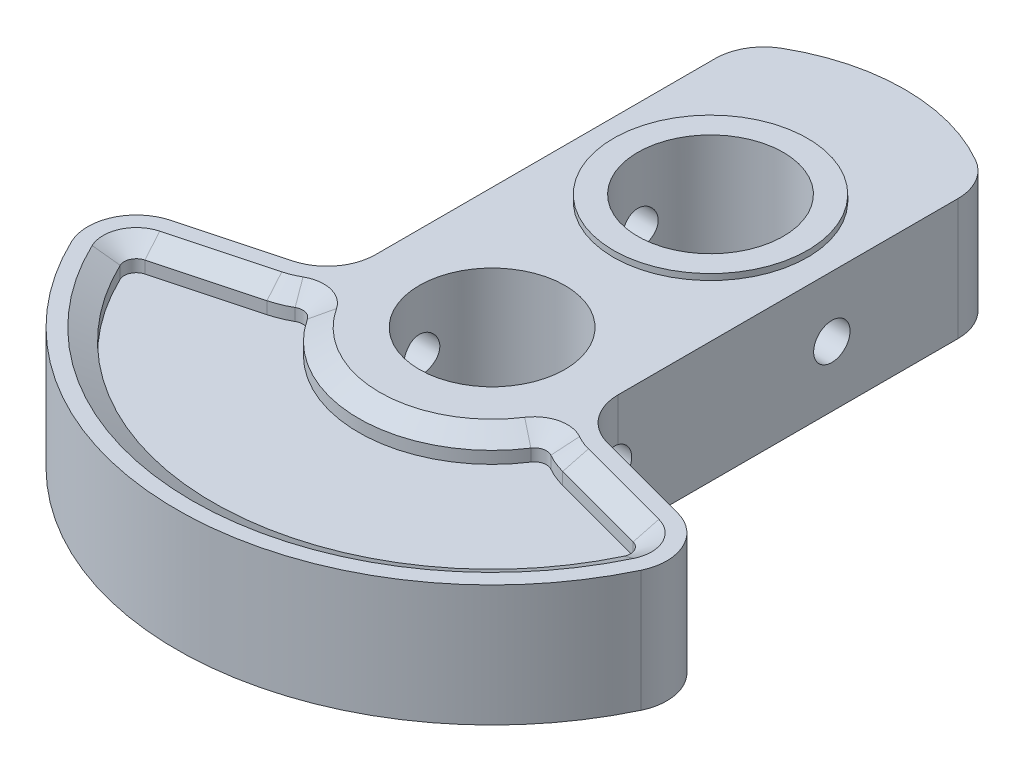
SolidWorks part; units mm, degrees
ref_plane "Front Plane" through (0, 0, 0) normal (0, 0, 1) x (1, 0, 0)
ref_plane "Top Plane" through (0, 0, 0) normal (0, 1, 0) x (1, 0, 0)
ref_plane "Right Plane" through (0, 0, 0) normal (1, 0, 0) x (0, 0, -1)
sketch "Sketch1" plane through (0, 0, 0) normal (0, 1, 0) x (1, 0, 0)
  line L0 (0, 41.1186) -> (0, -12.5062) construction
  line L1 (-10, 30.49) -> (-10, -2.6795)
  line L2 (10, 30.49) -> (10, -2.6795)
  line L3 (0, 0) -> (-25.1141, -6.7293) construction
  line L4 (-10, 41.1186) -> (-10, -12.5062) construction
  line L5 (10, 41.1186) -> (10, -12.5062) construction
  line L6 (0, 0) -> (25.1141, -6.7293) construction
  line L7 (-25.1141, -6.7293) -> (-10, -2.6795)
  line L8 (25.1141, -6.7293) -> (10, -2.6795)
  arc A0 (10, 30.49) -> (-10, 30.49) centre (0, 18) ccw
  arc A2 (-25.1141, -6.7293) -> (25.1141, -6.7293) centre (0, 0) ccw
  dimension "D1" = 18
  dimension "D2" = 10
  dimension "D4" = 26
  dimension "D5" = 75
  dimension "D6" = 75
  dimension "D3" = 10
extrude "Boss-Extrude1" add sketch "Sketch1" along normal mid plane 10
fillet "Fillet1" radius 4 6 edges at (-25.1141, 0, 6.7293) (-10, 0, 2.6795) (-10, 0, -30.49) (25.1141, 0, 6.7293) (10, 0, 2.6795) (10, 0, -30.49)
sketch "Sketch2" plane through (0, 0, 0) normal (0, 1, 0) x (1, 0, 0)
  circle A1 centre (0, 18) radius 8
  dimension "D1" = 18
extrude "Boss-Extrude2" add sketch "Sketch2" along normal mid plane 1
sketch "Sketch3" plane through (0, 5, 0) normal (0, 1, 0) x (1, 0, 0)
  circle A0 centre (0, 18) radius 8
  dimension "D1" = 18
extrude "Boss-Extrude3" add sketch "Sketch3" along normal mid plane 1
sketch "Sketch4" plane through (0, -5, 0) normal (0, -1, 0) x (1, 0, 0)
  circle A0 centre (0, 0) radius 8
extrude "Boss-Extrude4" add sketch "Sketch4" along normal mid plane 1
sketch "Sketch5" plane through (0, -5.5, 0) normal (0, -1, 0) x (-1, 0, 0)
  circle A0 centre (0, 0) radius 6
  circle A2 centre (0, 18) radius 6
extrude "Cut-Extrude1" cut sketch "Sketch5" against normal through all both
sketch "Sketch6" plane through (0, 5, 0) normal (0, 1, 0) x (1, 0, 0)
  line L0 (-12.9647, -3.4739) -> (-20.8962, -5.5991) construction
  line L6 (12.1883, -6.3717) -> (20.1197, -8.4969)
  line L7 (-20.1197, -8.4969) -> (-12.1883, -6.3717)
  line L8 (12.1883, -6.3717) -> (20.1197, -8.4969)
  line L9 (-20.1197, -8.4969) -> (-12.1883, -6.3717)
  arc A10 (-9.2082, -6.0173) -> (9.2082, -6.0173) centre (0, 0) ccw
  arc A11 (9.2082, -6.0173) -> (10.5397, -5.6951) centre (10.0453, -6.5644) cw
  arc A12 (-9.2082, -6.0173) -> (-10.5397, -5.6951) centre (-10.0453, -6.5644) ccw
  arc A15 (20.7637, -9.8929) -> (20.1197, -8.4969) centre (19.8609, -9.4628) ccw
  arc A16 (7, 0.3898) -> (12.1883, -6.3717) centre (14, 0.3898) ccw
  arc A17 (-12.1883, -6.3717) -> (-7, 0.3898) centre (-14, 0.3898) ccw
  arc A18 (-20.1197, -8.4969) -> (-20.7637, -9.8929) centre (-19.8609, -9.4628) ccw
  arc A19 (-20.7637, -9.8929) -> (20.7637, -9.8929) centre (0, 0) ccw
  arc A20 (20.7637, -9.8929) -> (20.1197, -8.4969) centre (19.8609, -9.4628) ccw
  arc A21 (10.5397, -5.6951) -> (12.1883, -6.3717) centre (14, 0.3898) ccw
  arc A22 (-12.1883, -6.3717) -> (-10.5397, -5.6951) centre (-14, 0.3898) ccw
  arc A23 (-20.1197, -8.4969) -> (-20.7637, -9.8929) centre (-19.8609, -9.4628) ccw
  arc A24 (-20.7637, -9.8929) -> (20.7637, -9.8929) centre (0, 0) ccw
  dimension "D2" = 1
  dimension "D1" = 3
extrude "Cut-Extrude2" cut sketch "Sketch6" against normal blind 2
mirror "Mirror7" about plane through (0, 0, 0) normal (0, 1, 0) of "Cut-Extrude2"
chamfer "Chamfer2" distance 1 angle 60 20 edges at (11.3424, 5, 6.0861) (9.8101, 5, 5.5924) (16.154, 5, 7.4343) (0, 5, 11) (20.7689, 5, 9.044) (-9.8101, 5, 5.5924) (0, 5, 23) (-11.3424, 5, 6.0861) (-20.7689, 5, 9.044) (-16.154, 5, 7.4343) (11.3424, -5, 6.0861) (9.8101, -5, 5.5924) (16.154, -5, 7.4343) (0, -5, 11) (20.7689, -5, 9.044) (-9.8101, -5, 5.5924) (0, -5, 23) (-11.3424, -5, 6.0861) (-20.7689, -5, 9.044) (-16.154, -5, 7.4343)
sketch "Sketch7" [suppressed] plane through (0, 0, 0) normal (1, 0, 0) x (0, 0, -1)
  circle A0 centre (0, 0) radius 1.5
  circle A1 centre (18, 0) radius 1.5
  dimension "D1" = 18
extrude "Cut-Extrude3" [suppressed] cut sketch "Sketch7" against normal through all both and the other way through all
sketch "Sketch9" plane through (0, 0, 0) normal (1, 0, 0) x (0, 0, -1)
  circle A0 centre (0, 0) radius 1.5
  circle A1 centre (18, 0) radius 1.5
  dimension "D2" = 3
  dimension "D1" = 18
extrude "Cut-Extrude4" cut sketch "Sketch9" against normal through all both and the other way through all
